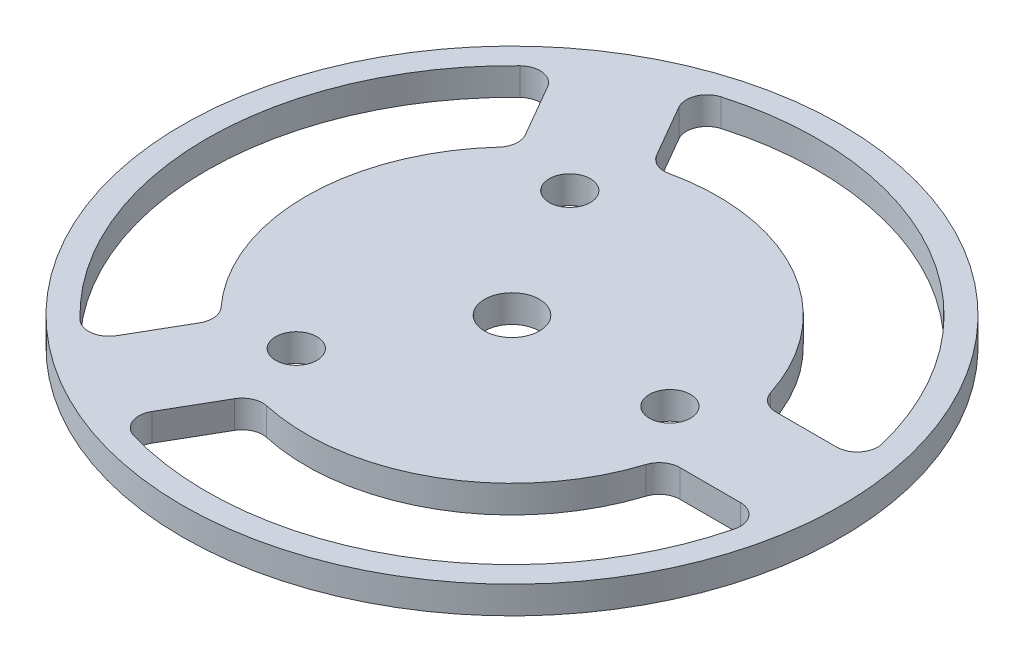
SolidWorks part; units mm, degrees
material "1060 Alloy"
ref_plane "Front Plane" through (0, 0, 0) normal (0, 0, 1) x (1, 0, 0)
ref_plane "Top Plane" through (0, 0, 0) normal (0, 1, 0) x (1, 0, 0)
ref_plane "Right Plane" through (0, 0, 0) normal (1, 0, 0) x (0, 0, -1)
sketch "Sketch1" plane through (0, 0, 0) normal (0, 1, 0) x (1, 0, 0)
  circle A0 centre (0, 0) radius 2
  circle A2 centre (0, 0) radius 24
  circle A3 centre (11.5, 0) radius 1.5
  circle A4 centre (-5.75, -9.9593) radius 1.5
  circle A5 centre (-5.75, 9.9593) radius 1.5
  point P13 (0, 0)
  dimension "D1" = 4
  dimension "D3" = 48
  dimension "D4" = 3
  dimension "D5" = 11.5
  dimension "D6" = 3
extrude "Boss-Extrude1" add sketch "Sketch1" along normal blind 2
sketch "Sketch2" plane through (0, 2, 0) normal (0, 1, 0) x (1, 0, 0)
  line L0 (21.973, 3.5) -> (14.586, 3.5)
  line L1 (21.973, -3.5) -> (14.586, -3.5)
  line L2 (-7.9554, -20.7792) -> (-4.2619, -14.3818)
  line L3 (-14.0176, -17.2792) -> (-10.3241, -10.8818)
  line L4 (-14.0176, 17.2792) -> (-10.3241, 10.8818)
  line L5 (-7.9554, 20.7792) -> (-4.2619, 14.3818)
  arc A0 (-14.0176, 17.2792) -> (-14.0176, -17.2792) centre (0, 0) ccw
  arc A1 (-10.3241, 10.8818) -> (-10.3241, -10.8818) centre (0, 0) ccw
  circle A2 centre (11.5, 0) radius 1.5 construction
  arc A3 (-4.2619, -14.3818) -> (14.586, -3.5) centre (0, 0) ccw
  arc A4 (-7.9554, -20.7792) -> (21.973, -3.5) centre (0, 0) ccw
  arc A5 (14.586, 3.5) -> (-4.2619, 14.3818) centre (0, 0) ccw
  arc A6 (21.973, 3.5) -> (-7.9554, 20.7792) centre (0, 0) ccw
  point P20 (0, 0)
  dimension "D1" = 44.5
  dimension "D2" = 30
  dimension "D3" = 3.5
  dimension "D4" = 3.5
  dimension "D5" = 3
extrude "Cut-Extrude1" cut sketch "Sketch2" against normal blind 2
fillet "Fillet1" radius 1.5 12 edges at (-4.2619, 1, 14.3818) (-7.9554, 1, -20.7792) (14.586, 1, 3.5) (21.973, 1, -3.5) (-14.0176, 1, 17.2792) (-4.2619, 1, -14.3818) (14.586, 1, -3.5) (-7.9554, 1, 20.7792) (21.973, 1, 3.5) (-10.3241, 1, 10.8818) (-10.3241, 1, -10.8818) (-14.0176, 1, -17.2792)
